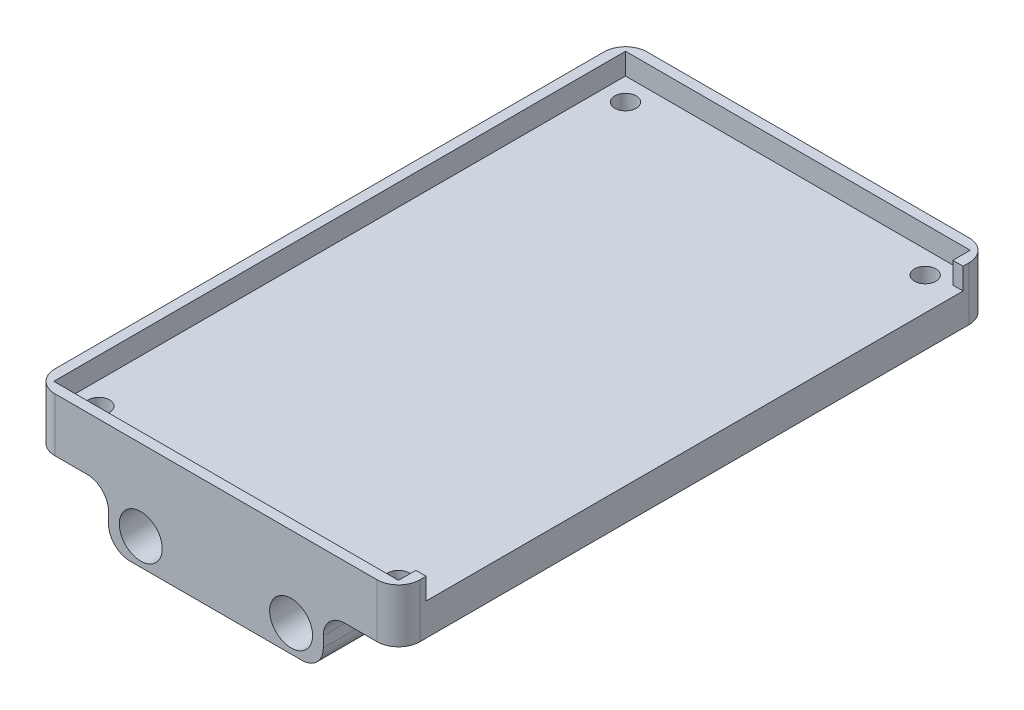
SolidWorks part; units mm, degrees
ref_plane "前视基准面" through (0, 0, 0) normal (0, 0, 1) x (1, 0, 0)
ref_plane "上视基准面" through (0, 0, 0) normal (0, 1, 0) x (1, 0, 0)
ref_plane "右视基准面" through (0, 0, 0) normal (1, 0, 0) x (0, 0, -1)
other "Configuration Table"
sketch "草图1" plane through (0, 0, 0) normal (0, 1, 0) x (1, 0, 0)
  line L1 (0, 0) -> (34, 0)
  line L2 (0, 0) -> (0, 55.14)
  line L3 (0, 55.14) -> (34, 55.14)
  line L4 (34, 0) -> (34, 55.14)
  dimension "D1" = 34
  dimension "D2" = 55.14
extrude "凸台-拉伸1" add sketch "草图1" along normal blind 5
sketch "草图2" plane through (0, 5, 0) normal (0, 1, 0) x (1, 0, 0)
  line L0 (0.95, 54.19) -> (33.05, 54.19)
  line L2 (0, 55.14) -> (0, 0)
  line L3 (0, 0) -> (34, 0)
  line L4 (34, 55.14) -> (34, 0)
  line L5 (33.05, 54.19) -> (33.05, 0.95)
  line L6 (0.95, 0.95) -> (33.05, 0.95)
  line L7 (0.95, 54.19) -> (0.95, 0.95)
  line L8 (0, 55.14) -> (34, 55.14) construction
  dimension "D1" = 0.95
extrude "切除-拉伸1" cut sketch "草图2" against normal blind 2 contours L0 L7 L6 L5
sketch "草图3" plane through (34, 0, 0) normal (1, 0, 0) x (0, 0, -1)
  line L0 (0, 5) -> (55.14, 5) construction
  line L1 (52.57, 10) -> (2.57, 10)
  line L2 (52.57, 10) -> (52.57, 0)
  line L3 (52.57, 0) -> (2.57, 0)
  line L4 (2.57, 10) -> (2.57, 0)
  line L5 (52.57, 10) -> (2.57, 0) construction
  line L6 (52.57, 0) -> (2.57, 10) construction
  line L7 (0, 0) -> (55.14, 0) construction
  point P0 (27.57, 5)
  dimension "D1" = 50
extrude "切除-拉伸2" cut sketch "草图3" against normal blind 2
fillet "圆角3" radius 2 1 edges at (0, 2.5, 0)
fillet "圆角4" radius 2 1 edges at (0, 2.5, -55.14)
fillet "圆角5" radius 2 1 edges at (34, 2.5, -55.14)
fillet "圆角6" radius 2 1 edges at (34, 2.5, 0)
sketch "草图5" plane through (0, 3, 0) normal (0, 1, 0) x (1, 0, 0)
  line L0 (17, -945.81) -> (17, 49054.19) construction
  line L1 (0.95, 54.19) -> (3.05, 54.19)
  line L2 (0.95, 54.19) -> (0.95, 52.09)
  line L3 (0.95, 52.09) -> (3.05, 52.09)
  line L4 (3.05, 54.19) -> (3.05, 52.09)
  line L6 (-999.05, 27.57) -> (49000.95, 27.57) construction
  line L7 (0.95, 54.19) -> (0.95, 0.95) construction
  line L8 (0.95, 54.19) -> (33.05, 54.19) construction
  circle A0 centre (3.05, 52.09) radius 1
  circle A1 centre (3.05, 3.05) radius 1
  circle A2 centre (30.95, 3.05) radius 1
  circle A3 centre (30.95, 52.09) radius 1
  point P13 (0.95, 27.57)
  point P16 (17, 54.19)
  dimension "D3" = 2
  dimension "D1" = 2.1
  dimension "D2" = 2.1
extrude "切除-拉伸3" cut sketch "草图5" against normal blind 5 contours A2 | A3 | A0 | A1
sketch "草图6" plane through (0, 3, 0) normal (0, 1, 0) x (1, 0, 0)
  line L0 (5.05, 49.09) -> (5.05, 6.05)
  line L1 (3.05, 52.09) -> (30.95, 52.09)
  line L2 (3.05, 52.09) -> (3.05, 3.05)
  line L3 (3.05, 3.05) -> (30.95, 3.05)
  line L4 (30.95, 52.09) -> (30.95, 3.05)
  line L5 (6.05, 5.05) -> (6.2547, 5.05)
  line L6 (28.95, 50.09) -> (28.95, 5.05)
  line L7 (6.05, 50.09) -> (6.2547, 50.09)
  line L8 (10.05, 49.09) -> (10.05, 6.05)
  line L13 (5.05, 50.09) -> (7.2547, 50.09)
  line L14 (5.05, 50.09) -> (5.05, 5.05)
  line L15 (5.05, 5.05) -> (7.2547, 5.05)
  line L16 (7.2547, 49.09) -> (7.2547, 6.05)
  line L17 (11.05, 50.09) -> (11.2547, 50.09)
  line L18 (12.2547, 49.09) -> (12.2547, 6.05)
  line L19 (11.05, 5.05) -> (11.2547, 5.05)
  line L20 (15.05, 49.09) -> (15.05, 6.05)
  line L21 (16.05, 50.09) -> (16.2547, 50.09)
  line L22 (17.2547, 49.09) -> (17.2547, 6.05)
  line L23 (16.05, 5.05) -> (16.2547, 5.05)
  line L24 (20.05, 49.09) -> (20.05, 6.05)
  line L25 (21.05, 50.09) -> (21.2547, 50.09)
  line L26 (22.2547, 49.09) -> (22.2547, 6.05)
  line L27 (21.05, 5.05) -> (21.2547, 5.05)
  line L28 (25.05, 49.09) -> (25.05, 6.05)
  line L29 (26.05, 50.09) -> (26.2547, 50.09)
  line L30 (27.2547, 49.09) -> (27.2547, 6.05)
  line L31 (26.05, 5.05) -> (26.2547, 5.05)
  line L32 (5.05, 50.09) -> (28.95, 50.09) construction
  line L33 (5.05, 5.05) -> (28.95, 5.05) construction
  line L34 (5.05, 50.09) -> (5.05, 5.05) construction
  arc A0 (6.2547, 50.09) -> (7.2547, 49.09) centre (6.2547, 49.09) cw
  arc A1 (6.2547, 5.05) -> (7.2547, 6.05) centre (6.2547, 6.05) ccw
  arc A2 (6.05, 5.05) -> (5.05, 6.05) centre (6.05, 6.05) cw
  arc A3 (5.05, 49.09) -> (6.05, 50.09) centre (6.05, 49.09) cw
  arc A4 (26.2547, 50.09) -> (27.2547, 49.09) centre (26.2547, 49.09) cw
  arc A5 (25.05, 49.09) -> (26.05, 50.09) centre (26.05, 49.09) cw
  arc A6 (26.2547, 5.05) -> (27.2547, 6.05) centre (26.2547, 6.05) ccw
  arc A7 (26.05, 5.05) -> (25.05, 6.05) centre (26.05, 6.05) cw
  arc A8 (21.2547, 5.05) -> (22.2547, 6.05) centre (21.2547, 6.05) ccw
  arc A9 (20.05, 6.05) -> (21.05, 5.05) centre (21.05, 6.05) ccw
  arc A10 (21.2547, 50.09) -> (22.2547, 49.09) centre (21.2547, 49.09) cw
  arc A11 (20.05, 49.09) -> (21.05, 50.09) centre (21.05, 49.09) cw
  arc A12 (16.2547, 50.09) -> (17.2547, 49.09) centre (16.2547, 49.09) cw
  arc A13 (15.05, 49.09) -> (16.05, 50.09) centre (16.05, 49.09) cw
  arc A14 (16.2547, 5.05) -> (17.2547, 6.05) centre (16.2547, 6.05) ccw
  arc A15 (16.05, 5.05) -> (15.05, 6.05) centre (16.05, 6.05) cw
  arc A16 (11.2547, 5.05) -> (12.2547, 6.05) centre (11.2547, 6.05) ccw
  arc A17 (10.05, 6.05) -> (11.05, 5.05) centre (11.05, 6.05) ccw
  arc A18 (11.2547, 50.09) -> (12.2547, 49.09) centre (11.2547, 49.09) cw
  arc A19 (10.05, 49.09) -> (11.05, 50.09) centre (11.05, 49.09) cw
  dimension "D3" = 1
  dimension "D4" = 1
  dimension "D1" = 2
  dimension "D2" = 5
extrude "切除-拉伸5" cut sketch "草图6" against normal blind 5 contours A3 L0 A2 L5 A1 L16 A0 L7 | A19 L8 A17 L19 A16 L18 A18 L17 | A11 L24 A9 L27 A8 L26 A10 L25 | A7 L31 A6 L30 A4 L29 A5 L28 | L20 A15 L23 A14 L22 A12 L21 A13
sketch "草图7" plane through (0, 0, 0) normal (0, -1, 0) x (1, 0, 0)
  line L1 (3.3369, -4.5252) -> (27.9146, -4.5252)
  line L2 (3.3369, -4.5252) -> (3.3369, -50.6148)
  line L3 (3.3369, -50.6148) -> (27.9146, -50.6148)
  line L4 (27.9146, -4.5252) -> (27.9146, -50.6148)
extrude "凸台-拉伸3" add sketch "草图7" against normal blind 3
sketch "草图8" plane through (0, 0, 0) normal (0, -1, 0) x (1, 0, 0)
  line L0 (17, 0) -> (17, -3)
  line L1 (2, 0) -> (32, 0) construction
  line L3 (7, -6) -> (27, -6)
  line L4 (7, -6) -> (7, 0)
  line L5 (7, 0) -> (27, 0)
  line L6 (27, -6) -> (27, 0)
  line L7 (7, -6) -> (27, 0) construction
  line L8 (7, 0) -> (27, -6) construction
  point P8 (0, 0)
  dimension "D1" = 3
  dimension "D2" = 6
  dimension "D3" = 20
extrude "凸台-拉伸5" add sketch "草图8" along normal blind 5
sketch "草图9" plane through (0, 0, 0) normal (0, -1, 0) x (1, 0, 0)
  line L0 (17, -55.14) -> (17, -52.14)
  line L1 (32, -55.14) -> (2, -55.14) construction
  line L3 (7, -55.14) -> (27, -55.14)
  line L4 (7, -55.14) -> (7, -49.14)
  line L5 (7, -49.14) -> (27, -49.14)
  line L6 (27, -55.14) -> (27, -49.14)
  line L7 (7, -55.14) -> (27, -49.14) construction
  line L8 (7, -49.14) -> (27, -55.14) construction
  dimension "D1" = 3
  dimension "D2" = 6
  dimension "D3" = 20
extrude "凸台-拉伸6" add sketch "草图9" along normal blind 5
sketch "草图10" plane through (0, 0, -55.14) normal (0, 0, -1) x (-1, 0, 0)
  line L1 (-27, -5) -> (-24, -5)
  line L2 (-27, -5) -> (-27, -2.5)
  line L3 (-27, -2.5) -> (-24, -2.5)
  line L4 (-24, -5) -> (-24, -2.5)
  line L5 (-7, -5) -> (-10, -5)
  line L6 (-7, -5) -> (-7, -2.5)
  line L7 (-7, -2.5) -> (-10, -2.5)
  line L8 (-10, -5) -> (-10, -2.5)
  circle A0 centre (-24, -2.5) radius 2
  circle A1 centre (-10, -2.5) radius 2
  dimension "D3" = 4
  dimension "D6" = 4
  dimension "D1" = 2.5
  dimension "D2" = 3
  dimension "D4" = 2.5
  dimension "D5" = 3
extrude "切除-拉伸6" cut sketch "草图10" against normal through all contours L7 A1 L8 | L8 A1 L7 | L3 A0 L4 | L4 A0 L3
fillet "圆角7" radius 2 1 edges at (7, -5, -52.14)
fillet "圆角8" radius 2 1 edges at (7, 0, -52.14)
fillet "圆角9" radius 2 1 edges at (27, -5, -52.14)
fillet "圆角10" radius 2 1 edges at (27, 0, -52.14)
fillet "圆角11" radius 2 1 edges at (7, -5, -3)
fillet "圆角12" radius 2 1 edges at (7, 0, -3)
fillet "圆角13" radius 2 1 edges at (27, -5, -3)
fillet "圆角14" radius 2 1 edges at (27, 0, -3)
sketch "草图11" plane through (0, 0, 0) normal (0, -1, 0) x (1, 0, 0)
  line L1 (32, -2.57) -> (34, -2.57)
  line L2 (32, -2.57) -> (32, -52.57)
  line L3 (32, -52.57) -> (34, -52.57)
  line L4 (34, -2.57) -> (34, -52.57)
extrude "凸台-拉伸7" add sketch "草图11" against normal blind 3
